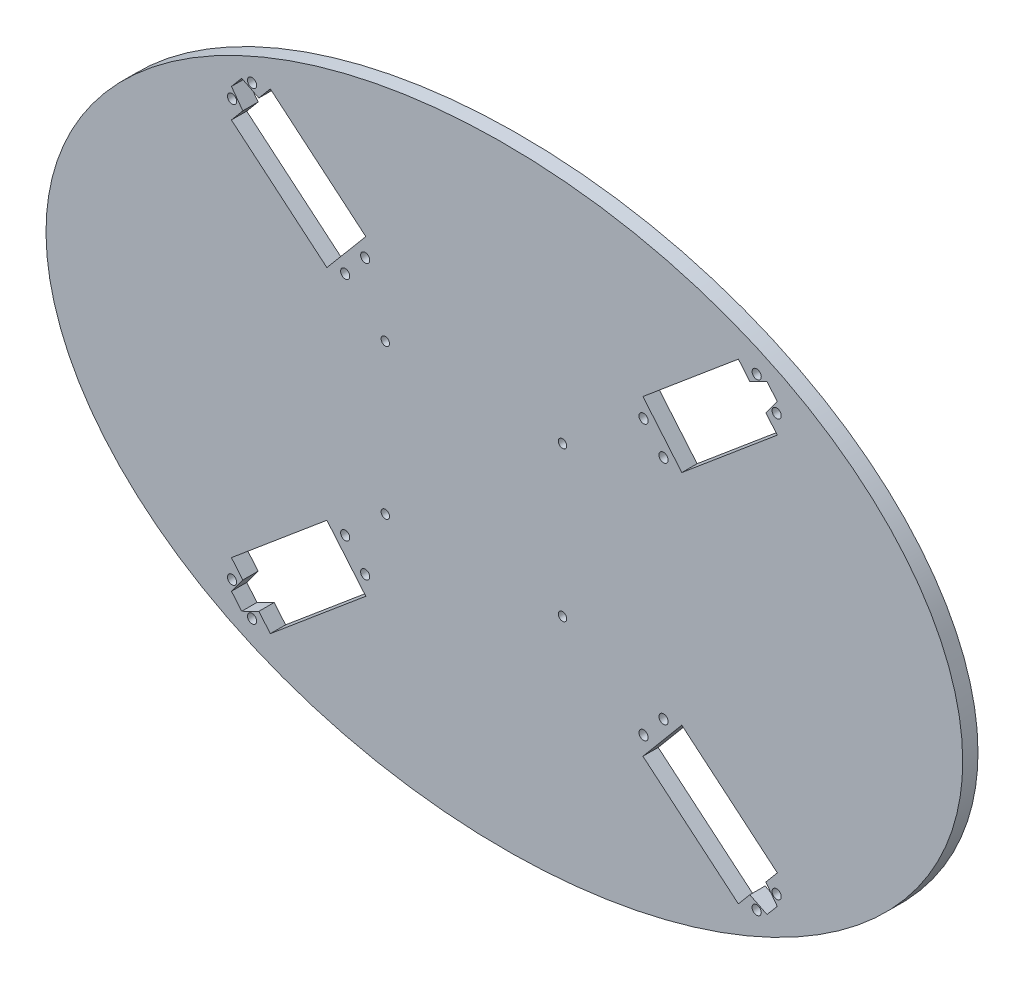
SolidWorks part; units mm, degrees
material "Plain Carbon Steel"
ref_plane "Front" through (0, 0, 0) normal (0, 0, 1) x (1, 0, 0)
ref_plane "Top" through (0, 0, 0) normal (0, 1, 0) x (1, 0, 0)
ref_plane "Right" through (0, 0, 0) normal (1, 0, 0) x (0, 0, -1)
ref_plane "Plane1" through (0, 0, 5) normal (0, 0, 1) x (1, 0, 0)
sketch "Sketch1" plane through (0, 0, 5) normal (0, 0, 1) x (1, 0, 0)
  ellipse E0 centre (0, 0) end of major axis (150, 0) minor radius 100
  point P0 (0, 0)
  point P1 (150, 0)
  point P2 (0, -100)
extrude "Boss-Extrude1" add sketch "Sketch1" against normal blind 5
sketch "Sketch18" plane through (0, 0, 5) normal (0, 0, 1) x (1, 0, 0)
  line L0 (0, 0) -> (-103.4154, -86.7758) construction
  line L1 (0, 0) -> (0, -156.5317) construction
  line L2 (0, 0) -> (-223.9538, 0) construction
  line L3 (-58.1228, -36.3601) -> (-52.0117, -43.643) construction
  line L4 (-89.3237, -62.0227) -> (-58.0739, -35.801)
  line L5 (-89.3237, -62.0227) -> (-76.5914, -77.1965)
  line L6 (-76.5914, -77.1965) -> (-45.3415, -50.9748)
  line L8 (-76.5424, -76.6374) -> (-45.9007, -50.9259) construction
  line L10 (-58.1228, -36.3601) -> (-88.7645, -62.0717) construction
  line L11 (-88.7645, -62.0717) -> (-76.5424, -76.6374) construction
  line L12 (-58.0739, -35.801) -> (-51.7077, -43.3879)
  line L13 (-51.7077, -43.3879) -> (-45.3415, -50.9748)
  line L14 (-52.0117, -43.643) -> (-45.9007, -50.9259) construction
  line L15 (-89.3237, 62.0227) -> (-76.5914, 77.1965)
  line L16 (-51.7077, 43.3879) -> (-45.3415, 50.9748)
  line L17 (-76.5914, 77.1965) -> (-45.3415, 50.9748)
  line L18 (-89.3237, 62.0227) -> (-58.0739, 35.801)
  line L19 (-58.0739, 35.801) -> (-51.7077, 43.3879)
  line L20 (51.7077, -43.3879) -> (45.3415, -50.9748)
  line L21 (58.0739, -35.801) -> (51.7077, -43.3879)
  line L22 (89.3237, -62.0227) -> (58.0739, -35.801)
  line L23 (89.3237, -62.0227) -> (76.5914, -77.1965)
  line L24 (76.5914, -77.1965) -> (45.3415, -50.9748)
  line L25 (58.0739, 35.801) -> (51.7077, 43.3879)
  line L26 (89.3237, 62.0227) -> (58.0739, 35.801)
  line L27 (76.5914, 77.1965) -> (45.3415, 50.9748)
  line L28 (51.7077, 43.3879) -> (45.3415, 50.9748)
  line L29 (89.3237, 62.0227) -> (76.5914, 77.1965)
  dimension "D1" = 50
  dimension "D2" = 19.0142
  dimension "D3" = 40
  dimension "D4" = 0.3969
  dimension "D5" = 0.3969
  dimension "D6" = 0.3969
extrude "Cut-Extrude2" cut sketch "Sketch18" against normal through all
sketch "Sketch19" plane through (0, 0, 5) normal (0, 0, 1) x (1, 0, 0)
  line L0 (-46.9026, -39.356) -> (-87.7626, -73.6416) construction
  line L1 (-47.2883, -38.8963) -> (-46.5169, -39.8156) construction
  line L2 (-87.3769, -74.1012) -> (-88.1483, -73.1819) construction
  line L3 (-67.3326, -56.4988) -> (-50.345, -76.7439) construction
  line L4 (0, 0) -> (-54.5322, 0) construction
  line L5 (0, 0) -> (0, -14.8757) construction
  line L6 (-67.3326, 56.4988) -> (-50.345, 76.7439) construction
  line L7 (-46.9026, 39.356) -> (-87.7626, 73.6416) construction
  line L8 (46.9026, 39.356) -> (87.7626, 73.6416) construction
  line L9 (67.3326, 56.4988) -> (50.345, 76.7439) construction
  line L10 (67.3326, -56.4988) -> (50.345, -76.7439) construction
  line L11 (46.9026, -39.356) -> (87.7626, -73.6416) construction
  circle A0 centre (-52.0933, -37.0699) radius 2.0936 construction
  circle A1 centre (-52.0933, -37.0699) radius 1.5
  circle A2 centre (-45.5526, -44.8648) radius 1.5
  circle A3 centre (-82.5719, -75.9276) radius 1.5
  circle A4 centre (-89.1126, -68.1327) radius 1.5
  circle A5 centre (-52.0933, 37.0699) radius 2.0936 construction
  circle A6 centre (-89.1126, 68.1327) radius 1.5
  circle A7 centre (-82.5719, 75.9276) radius 1.5
  circle A8 centre (-45.5526, 44.8648) radius 1.5
  circle A9 centre (-52.0933, 37.0699) radius 1.5
  circle A10 centre (52.0933, 37.0699) radius 2.0936 construction
  circle A11 centre (52.0933, -37.0699) radius 2.0936 construction
  circle A12 centre (52.0933, 37.0699) radius 1.5
  circle A13 centre (45.5526, 44.8648) radius 1.5
  circle A14 centre (82.5719, 75.9276) radius 1.5
  circle A15 centre (89.1126, 68.1327) radius 1.5
  circle A16 centre (89.1126, -68.1327) radius 1.5
  circle A17 centre (82.5719, -75.9276) radius 1.5
  circle A18 centre (45.5526, -44.8648) radius 1.5
  circle A19 centre (52.0933, -37.0699) radius 1.5
  dimension "D1" = 3
extrude "Cut-Extrude3" cut sketch "Sketch19" against normal through all
sketch "Sketch20" plane through (0, 0, 5) normal (0, 0, 1) x (1, 0, 0)
  line L0 (0, 0) -> (226.9653, 0) construction
  line L1 (0, 0) -> (0, 116.6876) construction
  point P2 (0, 0)
sketch "Sketch21" plane through (0, 0, 0) normal (0, 0, -1) x (-1, 0, 0)
  line L1 (89.3237, -62.0227) -> (85.5807, -66.4834) construction
  line L5 (85.5807, -66.4834) -> (89.3071, -71.5337)
  line L6 (89.3237, -62.0227) -> (76.5914, -77.1965) construction
  line L7 (89.3071, -71.5337) -> (85.955, -75.5286)
  line L8 (85.955, -75.5286) -> (80.3343, -72.7358)
  line L9 (80.3343, -72.7358) -> (85.5807, -66.4834)
  line L10 (89.3237, -62.0227) -> (89.3071, -71.5337) construction
  line L11 (85.955, -75.5286) -> (76.5914, -77.1965) construction
  line L12 (76.5914, -77.1965) -> (80.3343, -72.7358) construction
  dimension "D1" = 6.1008
extrude "Cut-Extrude4" cut sketch "Sketch21" against normal through all
mirror "Mirror1" about plane through (0, 0, 0) normal (0, 1, 0) of "Cut-Extrude4"
mirror "Mirror2" about plane through (0, 0, 0) normal (1, 0, 0) of "Mirror1", "Cut-Extrude4"
sketch "Sketch22" plane through (0, 0, 5) normal (0, 0, 1) x (1, 0, 0)
  circle A0 centre (-38.9621, -24.5) radius 1.375
  circle A1 centre (19.0379, -24.5) radius 1.375
  circle A2 centre (19.0379, 24.5) radius 1.375
  circle A3 centre (-38.9621, 24.5) radius 1.375
extrude "Cut-Extrude5" cut sketch "Sketch22" against normal through all
